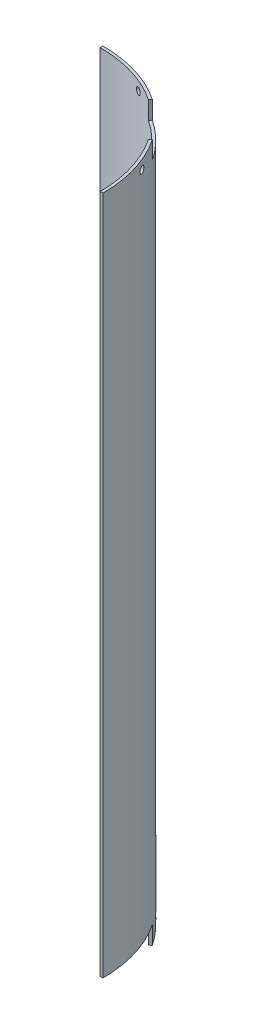
SolidWorks part; units mm, degrees
material "1060 Alloy"
ref_plane "Front Plane" through (0, 0, 0) normal (0, 0, 1) x (1, 0, 0)
ref_plane "Top Plane" through (0, 0, 0) normal (0, 1, 0) x (1, 0, 0)
ref_plane "Right Plane" through (0, 0, 0) normal (1, 0, 0) x (0, 0, -1)
sketch "Sketch1" plane through (0, 0, 0) normal (0, 1, 0) x (1, 0, 0)
  line L0 (0, 0) -> (0, 92)
  line L1 (0, 0) -> (92, 0)
  circle A0 centre (0, 0) radius 90
  circle A1 centre (0, 0) radius 92
  dimension "Internal Diameter" = 180
  dimension "External Diameter" = 184
extrude "Boss-Extrude1" add sketch "Sketch1" along normal blind 504 contours L1 A1 L0 A0
ref_plane "Plane1" through (0, 6.5, 0) normal (0, -1, 0) x (-1, 0, 0)
sketch "Sketch2" plane through (0, 6.5, 0) normal (0, -1, 0) x (-1, 0, 0)
  line L0 (0, 0) -> (-84.9969, 35.2069)
  line L1 (0, 0) -> (-65.0538, 65.0538)
  line L2 (0, 0) -> (-92, 0) construction
  line L3 (0, 0) -> (-35.2069, 84.9969)
  arc A0 (0, 92) -> (-92, 0) centre (0, 0) ccw construction
  dimension "D1" = 135
  dimension "D2" = 22.5
ref_plane "Plane2" through (84.9969, 0, -35.2069) normal (0.9239, 0, -0.3827) x (-0.3827, 0, -0.9239)
ref_plane "Plane3" through (35.2069, 0, -84.9969) normal (0.3827, 0, -0.9239) x (-0.9239, 0, -0.3827)
sketch "Sketch3" plane through (84.9969, 0, -35.2069) normal (0.9239, 0, -0.3827) x (-0.3827, 0, -0.9239)
  circle A0 centre (0, 6.5) radius 2.5
  point P0 (0, 6.5)
  dimension "Right Hole Diameter" = 5
sketch "Sketch5" plane through (35.2069, 0, -84.9969) normal (0.3827, 0, -0.9239) x (-0.9239, 0, -0.3827)
  line L0 (0, 6.5) -> (-84.9969, 6.5) construction
  circle A0 centre (0, 6.5) radius 2.5
  dimension "Left Hole Diameter" = 5
ref_plane "Plane4" through (65.0538, 0, -65.0538) normal (0.7071, 0, -0.7071) x (-0.7071, 0, -0.7071)
sketch "Sketch6" plane through (65.0538, 0, -65.0538) normal (0.7071, 0, -0.7071) x (-0.7071, 0, -0.7071)
  line L0 (0, 6.5) -> (-65.0538, 6.5) construction
  line L1 (0, 6.5) -> (35.2069, 6.5) construction
  circle A0 centre (0, 6.5) radius 2.5
  dimension "Middle Hole Diameter" = 5
extrude "Cut-Extrude4" cut sketch "Sketch6" against normal up to surface (2.0347 mm away)
extrude "Cut-Extrude2" cut sketch "Sketch3" against normal up to surface (2.0347 mm away) contours A0
extrude "Cut-Extrude3" cut sketch "Sketch5" against normal up to surface (2.0347 mm away) contours A0
pattern_linear "LPattern2" count 2 spacing 491 along (0, 1, 0) of "Cut-Extrude4", "Cut-Extrude2", "Cut-Extrude3"
sketch "Sketch7" plane through (0, 0, 0) normal (0, -1, 0) x (1, 0, 0)
  line L0 (0, 0) -> (65.0538, -65.0538) construction
  line L1 (0.3118, -0.3118) -> (57.9282, -0.3118) construction
  line L2 (0.3118, -0.3118) -> (76.4474, -51.184)
  line L3 (0.3118, -0.3118) -> (51.184, -76.4474)
  line L6 (92, 0) -> (90, 0)
  line L7 (0, -90) -> (0, -92)
  line L8 (92, 0) -> (90, 0)
  line L9 (0, -90) -> (0, -92)
  arc A0 (0, -92) -> (92, 0) centre (0, 0) ccw construction
  arc A2 (0, -90) -> (90, 0) centre (0, 0) ccw
  arc A3 (0, -92) -> (92, 0) centre (0, 0) ccw
  arc A4 (0, -90) -> (90, 0) centre (0, 0) ccw
  arc A5 (0, -92) -> (92, 0) centre (0, 0) ccw
  arc M5 (90, 0) -> (0, -90) centre (0, 0) cw
  arc M7 (0, -92) -> (92, 0) centre (0, 0) ccw
  dimension "D1" = 45
  dimension "D2" = 11.25
  dimension "D3" = 0
extrude "Cut-Extrude5" cut sketch "Sketch7" against normal blind 13 contours L3 L2 M5 M7
sketch "Sketch9" plane through (0, 504, 0) normal (0, 1, 0) x (1, 0, 0)
  line L0 (0, 0) -> (92, 0)
  line L1 (0, 0) -> (65.0538, 65.0538) construction
  line L2 (0, 0) -> (51.1125, 76.4952)
  line L3 (0, 0) -> (76.4952, 51.1125)
  line L4 (0, 0) -> (0, 92)
  line L7 (90, 0) -> (92, 0)
  line L8 (0, 92) -> (0, 90)
  line L9 (90, 0) -> (92, 0)
  line L10 (0, 92) -> (0, 90)
  arc A2 (92, 0) -> (0, 92) centre (0, 0) ccw
  arc A3 (90, 0) -> (0, 90) centre (0, 0) ccw
  arc A4 (92, 0) -> (0, 92) centre (0, 0) ccw
  arc A5 (90, 0) -> (0, 90) centre (0, 0) ccw
  line M4 (90, 0) -> (92, 0)
  arc M5 (92, 0) -> (0, 92) centre (0, 0) ccw
  line M6 (0, 92) -> (0, 90)
  arc M7 (0, 90) -> (90, 0) centre (0, 0) cw
  dimension "D1" = 45
  dimension "D2" = 11.25
  dimension "D3" = 0
extrude "Cut-Extrude6" cut sketch "Sketch9" against normal blind 13 contours L2 M7 M5 M6 | L3 M7 M4 M5
move or copy body "Body-Move/Copy1" bodies to move or copy 108 copy no rotation origin (0, 252, 0) rotation axis (0.7071, 0, -0.7071) rotation angle 180
equation "\"Total Panel Length\"= 504"
equation "\"Internal Panel Diameter\"= 180"
equation "\"External Panel Diameter\"= 184"
equation "\"L & R Mounting Hole Diameter\"= 5"
equation "\"M Mounting Hole DIameter\"= 5"
equation "\"Mounting Hole Dist. from Top\"= 6.5"
equation "\"Mounting Hole Dist. from Base\"= 6.5"
equation "\"External Diameter@Sketch1\"= \"External Panel Diameter\""
equation "\"Internal Diameter@Sketch1\"= \"Internal Panel Diameter\""
equation "\"Panel Length@Boss-Extrude1\"= \"Total Panel Length\""
equation "\"Right Hole Diameter@Sketch3\"= \"L & R Mounting Hole Diameter\""
equation "\"Left Hole Diameter@Sketch5\"= \"L & R Mounting Hole Diameter\""
equation "\"Middle Hole Diameter@Sketch6\" = \"M Mounting Hole DIameter\""
equation "\"Mounting from Top@Plane1\"= \"Mounting Hole Dist. from Top\""
equation "\"Mounting from Base@LPattern2\"= \"Total Panel Length\" - \"Mounting Hole Dist. from Base\" - \"Mounting Hole Dist. from Top\""
equation "\"Top Tab Length@Cut-Extrude5\" = \"Top Tab Length\""
equation "\"Base Tab Length@Cut-Extrude6\"= \"Base Tab Length\""
equation "\"Top Tab Length\"= 13"
equation "\"Base Tab Length\"= 13"
